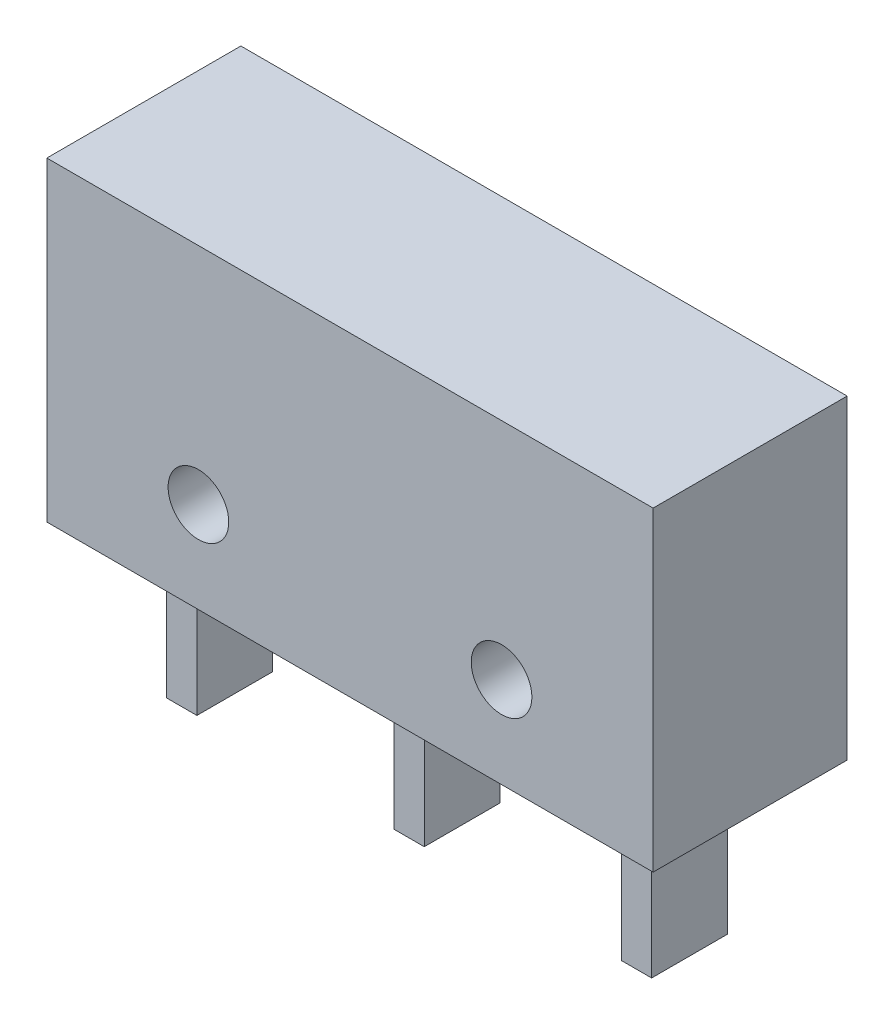
SolidWorks part; units mm, degrees
ref_plane "Plan de face" through (0, 0, 0) normal (0, 0, 1) x (1, 0, 0)
ref_plane "Plan de dessus" through (0, 0, 0) normal (0, 1, 0) x (1, 0, 0)
ref_plane "Plan de droite" through (0, 0, 0) normal (1, 0, 0) x (0, 0, -1)
sketch "Esquisse1" plane through (0, 0, 0) normal (0, 0, 1) x (1, 0, 0)
  line L0 (-12.1708, -2.2) -> (15.3849, -2.2) construction
  line L1 (-10, -5.2) -> (10, -5.2)
  line L2 (-10, -5.2) -> (-10, 5.2)
  line L3 (-10, 5.2) -> (10, 5.2)
  line L4 (10, -5.2) -> (10, 5.2)
  line L5 (-10, -5.2) -> (10, 5.2) construction
  line L6 (-10, 5.2) -> (10, -5.2) construction
  circle A0 centre (-5, -2.2) radius 1
  circle A1 centre (5, -2.2) radius 1
  point P0 (0, 0)
  dimension "D4" = 2
  dimension "D5" = 2
  dimension "D6" = 5
  dimension "D7" = 10
  dimension "D1" = 10.4
  dimension "D2" = 20
  dimension "D3" = 3
extrude "Boss.-Extru.1" add sketch "Esquisse1" along normal blind 6.4
sketch "Esquisse2" plane through (0, -5.2, 0) normal (0, -1, 0) x (1, 0, 0)
  line L0 (-10, 3.2) -> (10, 3.2) construction
  line L1 (-10, 6.4) -> (-10, 0) construction
  line L2 (10, 6.4) -> (10, 0) construction
  line L4 (-8, 4.45) -> (-7, 4.45)
  line L5 (-8, 4.45) -> (-8, 1.95)
  line L6 (-8, 1.95) -> (-7, 1.95)
  line L7 (-7, 4.45) -> (-7, 1.95)
  line L8 (-8, 4.45) -> (-7, 1.95) construction
  line L9 (-8, 1.95) -> (-7, 4.45) construction
  line L10 (-0.5, 4.45) -> (0.5, 4.45)
  line L11 (-0.5, 4.45) -> (-0.5, 1.95)
  line L12 (-0.5, 1.95) -> (0.5, 1.95)
  line L13 (0.5, 4.45) -> (0.5, 1.95)
  line L14 (-0.5, 4.45) -> (0.5, 1.95) construction
  line L15 (-0.5, 1.95) -> (0.5, 4.45) construction
  line L16 (7, 4.45) -> (8, 4.45)
  line L17 (7, 4.45) -> (7, 1.95)
  line L18 (7, 1.95) -> (8, 1.95)
  line L19 (8, 4.45) -> (8, 1.95)
  line L20 (7, 4.45) -> (8, 1.95) construction
  line L21 (7, 1.95) -> (8, 4.45) construction
  point P6 (-7.5, 3.2)
  point P11 (0, 3.2)
  point P16 (7.5, 3.2)
  dimension "D1" = 2.5
  dimension "D2" = 2.5
  dimension "D3" = 1
  dimension "D4" = 1
  dimension "D5" = 1
  dimension "D6" = 2.5
  dimension "D7" = 2.5
  dimension "D8" = 2.5
extrude "Boss.-Extru.2" add sketch "Esquisse2" along normal blind 5
